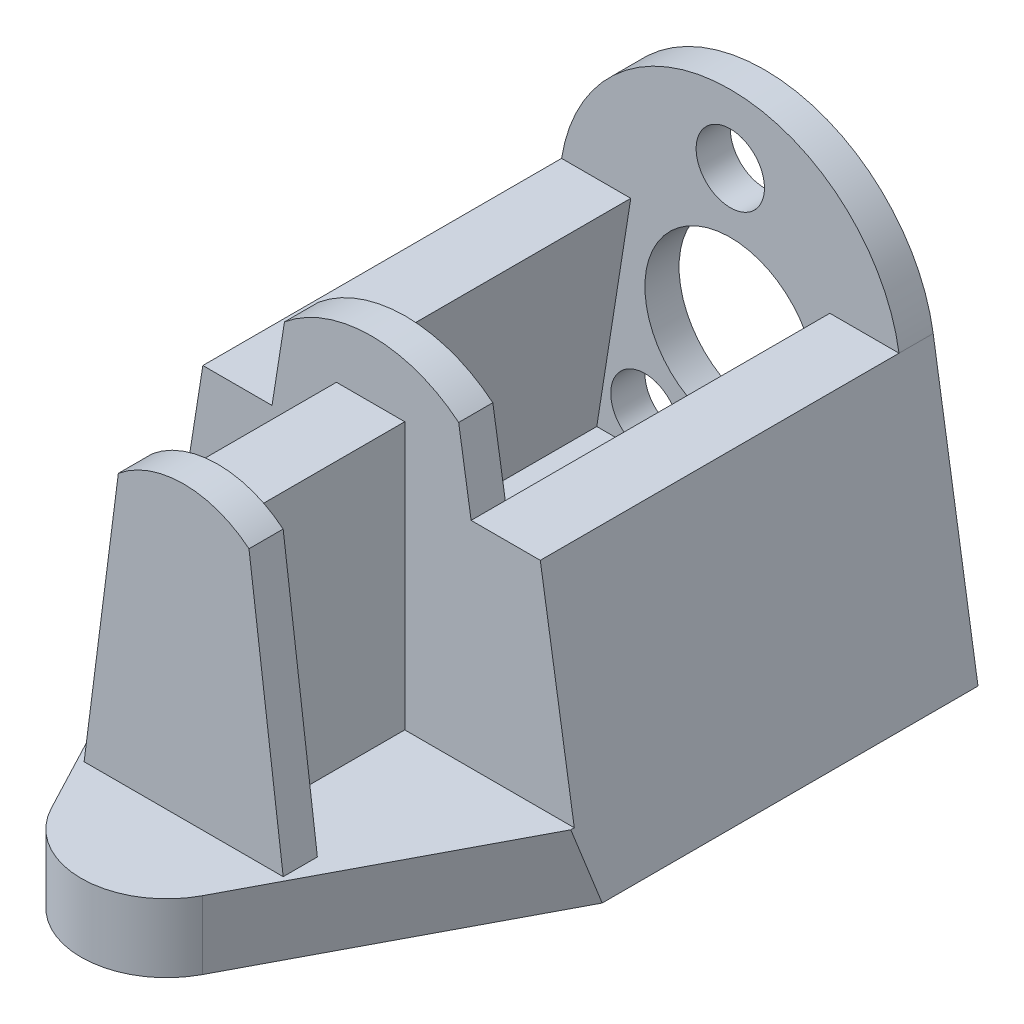
SolidWorks part; units mm, degrees
ref_plane "Front Plane" through (0, 0, 0) normal (0, 0, 1) x (1, 0, 0)
ref_plane "Top Plane" through (0, 0, 0) normal (0, 1, 0) x (1, 0, 0)
ref_plane "Right Plane" through (0, 0, 0) normal (1, 0, 0) x (0, 0, -1)
sketch "Sketch1" plane through (0, 0, 0) normal (0, 0, 1) x (1, 0, 0)
  line L0 (-12.5, 0) -> (12.5, 0)
  line L1 (0, 0) -> (0, 25) construction
  line L2 (-12.5, 0) -> (-9.8769, 16.5641)
  line L3 (12.5, 0) -> (9.8769, 16.5641)
  line L4 (-5, 6.1) -> (5, 6.1)
  arc A0 (9.8769, 16.5641) -> (-9.8769, 16.5641) centre (0, 15) ccw
  circle A1 centre (0, 12.5) radius 5
  circle A2 centre (5, 6.1) radius 2
  circle A3 centre (-5, 6.1) radius 2
  circle A4 centre (0, 21) radius 2
  point P4 (0, 0)
  point P14 (0, 6.1)
  dimension "D3" = 20
  dimension "D4" = 10
  dimension "D5" = 4
  dimension "D8" = 4
  dimension "D9" = 4
  dimension "D1" = 25
  dimension "D2" = 25
  dimension "D6" = 10
  dimension "D7" = 6.1
extrude "Boss-Extrude1" add sketch "Sketch1" along normal blind 2
ref_plane "Plane1" through (0, 0, 50) normal (0, 0, -1) x (-1, 0, 0)
sketch "Sketch2" plane through (0, 0, 50) normal (0, 0, -1) x (-1, 0, 0)
  line L0 (12.5, 0) -> (-12.5, 0) construction
  line L1 (12.5, 0) -> (-12.5, 0)
  line L2 (-11.8666, 4) -> (11.8666, 4)
  line L3 (-12.5, 0) -> (-9.8769, 16.5641) construction
  line L4 (12.5, 0) -> (9.8769, 16.5641) construction
  line L5 (11.8666, 4) -> (12.5, 0)
  line L6 (-11.8666, 4) -> (-12.5, 0)
  dimension "D1" = 4
extrude "Boss-Extrude2" add sketch "Sketch2" along normal up to surface (48 mm away) up to face at (5, 12.5, 2)
ref_plane "Plane2" through (0, 0, 22) normal (0, 0, 1) x (1, 0, 0)
sketch "Sketch3" plane through (0, 0, 22) normal (0, 0, 1) x (1, 0, 0)
  line L0 (-5.9262, 15.9385) -> (-7.1833, 8)
  line L2 (7.1833, 8) -> (5.9262, 15.9385)
  line L3 (-11.8666, 4) -> (11.8666, 4)
  line L4 (11.8666, 4) -> (9.8769, 16.5641)
  line L5 (-9.8769, 16.5641) -> (-11.8666, 4)
  line L6 (-11.8666, 4) -> (11.8666, 4)
  line L7 (11.8666, 4) -> (9.8769, 16.5641)
  line L8 (-9.8769, 16.5641) -> (-11.8666, 4)
  line L9 (-5.9262, 15.9385) -> (-5.0985, 21.1648)
  line L10 (5.9262, 15.9385) -> (5.0985, 21.1648)
  line L11 (-7.1833, 8) -> (-7.8167, 4)
  line L12 (7.1833, 8) -> (7.8173, 3.9961)
  line L14 (-7.1833, 8) -> (7.1833, 8) construction
  arc A0 (5.9262, 15.9385) -> (-5.9262, 15.9385) centre (0, 15) ccw
  arc A1 (9.8769, 16.5641) -> (-9.8769, 16.5641) centre (0, 15) ccw
  arc A2 (9.8769, 16.5641) -> (-9.8769, 16.5641) centre (0, 15) ccw
  arc A3 (5.0985, 21.1648) -> (-5.0985, 21.1648) centre (0, 15) ccw
  arc A4 (7.9015, 16.2513) -> (-7.9015, 16.2513) centre (0, 15) ccw construction
  dimension "D1" = 0
  dimension "D2" = 4
  dimension "D3" = 2
extrude "Boss-Extrude3" add sketch "Sketch3" along normal mid plane 2 contours L2 A0 L0 L11 L6 L12 | L10 A3 L9 A0
sketch "Sketch4" plane through (0, 4, 0) normal (0, 1, 0) x (1, 0, 0)
  line L0 (0, 0) -> (0, -40) construction
  line L1 (9.8769, 0) -> (-9.8769, 0) construction
  line L2 (-12.5, -22) -> (-4.4237, -37.3305)
  line L3 (-11.55, -22) -> (11.55, -22) construction
  line L4 (-12.5, -50) -> (-12.5, 0) construction
  line L5 (12.5, -22) -> (4.4237, -37.3305)
  line L6 (-12.5, -22) -> (-16.1874, -22)
  line L7 (-16.1874, -22) -> (-16.1874, -58.3918)
  line L8 (-16.1874, -58.3918) -> (30.8202, -58.3918)
  line L9 (30.8202, -58.3918) -> (16.182, -36.9885)
  line L10 (16.182, -36.9885) -> (16.182, -22)
  line L11 (16.182, -22) -> (12.5, -22)
  arc A0 (-4.4237, -37.3305) -> (4.4237, -37.3305) centre (0, -35) ccw
  dimension "D1" = 10
  dimension "D2" = 35
extrude "Cut-Extrude2" cut sketch "Sketch4" against normal blind 36
sketch "Sketch6" plane through (0, 0, 2) normal (0, 0, 1) x (1, 0, 0)
  line L0 (11.8666, 4) -> (7.8666, 4)
  line L1 (11.8666, 4) -> (-11.8666, 4) construction
  line L2 (11.8666, 4) -> (9.8769, 16.5641) construction
  line L3 (11.8666, 4) -> (9.8769, 16.5641)
  line L4 (9.8769, 16.5641) -> (5.8271, 16.5641)
  line L5 (7.8167, 4) -> (5.0985, 21.1648)
  line L6 (-5.0985, 21.1648) -> (-7.8167, 4)
  line L7 (-7.8167, 4) -> (7.8167, 4)
  line L8 (7.8167, 4) -> (5.0985, 21.1648)
  line L9 (-5.0985, 21.1648) -> (-7.8167, 4)
  line L10 (-7.8167, 4) -> (7.8167, 4)
  line L11 (0, 0) -> (0, 18.5751) construction
  line L12 (-11.8666, 4) -> (-9.8769, 16.5641)
  line L13 (-7.8167, 4) -> (-5.0985, 21.1648)
  line L14 (-11.8666, 4) -> (-7.8666, 4)
  line L15 (-9.8769, 16.5641) -> (-5.8271, 16.5641)
  arc A1 (5.0985, 21.1648) -> (-5.0985, 21.1648) centre (0, 15) ccw
  arc A2 (5.0985, 21.1648) -> (-5.0985, 21.1648) centre (0, 15) ccw
  line M9 (-11.8666, 4) -> (11.8666, 4)
  line M10 (11.8666, 4) -> (9.8769, 16.5641)
  line M12 (-9.8769, 16.5641) -> (-11.8666, 4)
  dimension "D1" = 4
  dimension "D2" = 0
extrude "Boss-Extrude4" add sketch "Sketch6" along normal blind 21 contours L15 L13 M12 M9 | L8 L4 M9 M10
ref_plane "Plane3" through (0, 0, 33) normal (0, 0, 1) x (1, 0, 0)
sketch "Sketch7" plane through (0, 0, 33) normal (0, 0, 1) x (1, 0, 0)
  line L0 (-3.8239, 19.6236) -> (-5.8271, 4)
  line L1 (0, 0) -> (0, 29.2842) construction
  line L2 (3.8239, 19.6236) -> (5.8271, 4)
  line L5 (7.8167, 4) -> (5.8271, 16.5641)
  line L6 (-7.8167, 4) -> (7.8167, 4)
  line L7 (-5.8271, 16.5641) -> (-7.8167, 4)
  line L8 (-5.0985, 21.1648) -> (-5.8271, 16.5641)
  line L9 (5.8271, 16.5641) -> (5.0985, 21.1648)
  line L10 (7.8167, 4) -> (5.8271, 16.5641)
  line L11 (-7.8167, 4) -> (7.8167, 4)
  line L12 (-5.8271, 16.5641) -> (-7.8167, 4)
  line L13 (-5.0985, 21.1648) -> (-5.8271, 16.5641)
  line L14 (5.8271, 16.5641) -> (5.0985, 21.1648)
  arc A0 (3.8239, 19.6236) -> (-3.8239, 19.6236) centre (0, 15) ccw
  arc A1 (5.0985, 21.1648) -> (-5.0985, 21.1648) centre (0, 15) ccw
  arc A2 (5.0985, 21.1648) -> (-5.0985, 21.1648) centre (0, 15) ccw
  dimension "D2" = 6
  dimension "D1" = 0
extrude "Boss-Extrude5" add sketch "Sketch7" along normal mid plane 2 contours L1 L11 L2 A0 | L11 L1 A0 L0
sketch "Sketch8" plane through (0, 0, 32) normal (0, 0, -1) x (-1, 0, 0)
  line L0 (4.4237, 4) -> (-4.4237, 4) construction
  line L1 (2.0576, 4) -> (-1.9424, 4)
  line L2 (2.0576, 4) -> (2.0576, 19.6236)
  line L3 (2.0576, 19.6236) -> (-1.9424, 19.6236)
  line L4 (-1.9424, 4) -> (-1.9424, 19.6236)
  line L5 (2.0576, 4) -> (-1.9424, 19.6236) construction
  line L6 (2.0576, 19.6236) -> (-1.9424, 4) construction
  line L7 (3.8239, 19.6236) -> (-0.9474, 19.6236) construction
  point P0 (0.0576, 11.8118)
  dimension "D1" = 4
extrude "Boss-Extrude6" add sketch "Sketch8" along normal up to surface (9 mm away) up to face at (0, 14.8027, 23)
sketch "Sketch9" plane through (0, 0, 0) normal (0, 0, -1) x (-1, 0, 0)
  circle A0 centre (0, 12.5) radius 2.3787
ref_plane "Plane4" through (0, 12.5, 0) normal (0, 1, 0) x (1, 0, 0)
sketch "Sketch10" plane through (0, 12.5, 0) normal (0, 1, 0) x (1, 0, 0)
  line L0 (0, 0) -> (0, -20) construction
sketch "Sketch11" plane through (0, 0, 0) normal (0, -1, 0) x (1, 0, 0)
  line L0 (0, 0) -> (0, 40) construction
  line L1 (0, 0) -> (0, 20) construction
  arc A0 (4.4237, 37.3305) -> (-4.4237, 37.3305) centre (0, 35) ccw construction
  circle A1 centre (0, 10) radius 5
  circle A2 centre (0, 10) radius 2.5
  dimension "D1" = 10
  dimension "D2" = 5
extrude "Boss-Extrude7" add sketch "Sketch11" along normal blind 5
